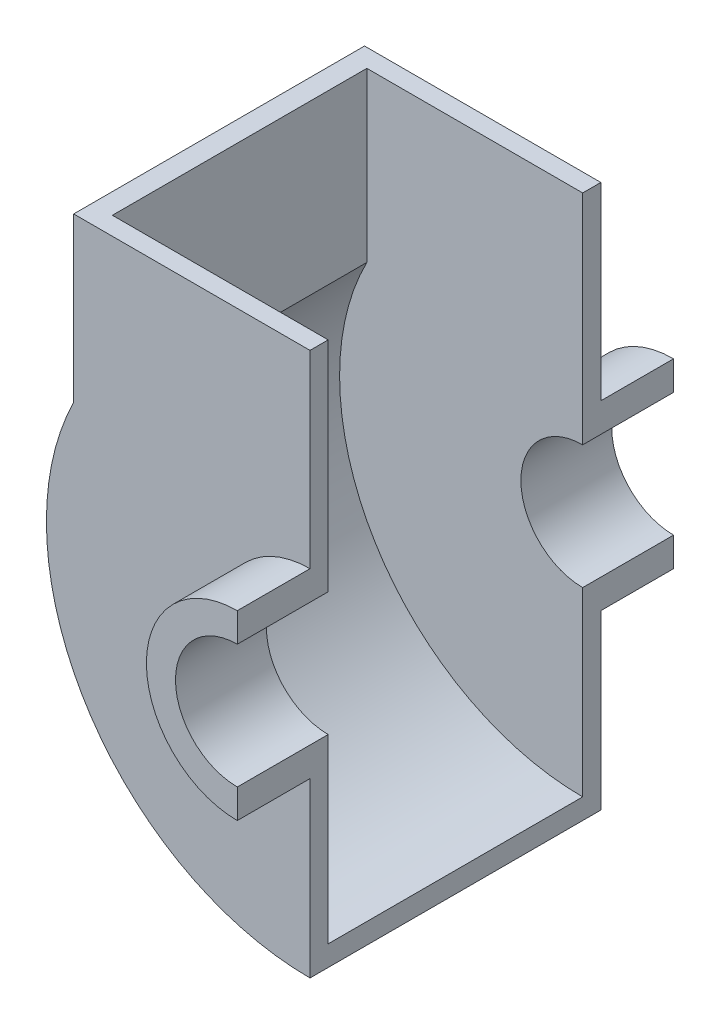
SolidWorks part; units mm, degrees
material "AISI 316 Annealed Stainless Steel Bar (SS)"
ref_plane "Front Plane" through (0, 0, 0) normal (0, 0, 1) x (1, 0, 0)
ref_plane "Top Plane" through (0, 0, 0) normal (0, 1, 0) x (1, 0, 0)
ref_plane "Right Plane" through (0, 0, 0) normal (1, 0, 0) x (0, 0, -1)
sketch "Sketch1" plane through (0, 0, 0) normal (0, 0, 1) x (1, 0, 0)
  line L1 (0, 25) -> (0, 17)
  line L2 (0, -17) -> (0, -25)
  arc A0 (0, 25) -> (0, -25) centre (0, 0) ccw
  arc A1 (0, 17) -> (0, -17) centre (0, 0) ccw
  dimension "D1" = 34
  dimension "D2" = 50
extrude "Boss-Extrude1" add sketch "Sketch1" along normal blind 20 and the other way blind 5
sketch "Sketch2" plane through (0, 0, 0) normal (0, 0, 1) x (1, 0, 0)
  line L0 (0, 25) -> (0, 77)
  line L1 (0, 77) -> (-65, 77)
  line L2 (-65, 77) -> (-65, 32.1131)
  line L3 (0, -25) -> (0, -72.5)
  arc A0 (-65, 32.1131) -> (0, -72.5) centre (0, 0) ccw
  arc A1 (0, 25) -> (0, -25) centre (0, 0) ccw construction
  arc A2 (0, 25) -> (0, -25) centre (0, 0) ccw
  point P11 (0, 77.1882)
  point P12 (-76.2824, 74.7729)
  point P13 (-77.2888, 90.9351)
  dimension "D1" = 145
  dimension "D2" = 52
  dimension "D3" = 65
extrude "Boss-Extrude2" add sketch "Sketch2" against normal blind 5
ref_plane "Plane1" through (0, 0, -40) normal (0, 0, 1) x (1, 0, 0)
mirror "Mirror4" about plane through (0, 0, -40) normal (0, 0, 1) of bodies 102
sketch "Sketch3" plane through (0, 0, -80) normal (0, 0, -1) x (-1, 0, 0)
  line L0 (65, 77) -> (65, 32.1131) construction
  line L1 (65, 77) -> (65, 32.1131)
  line L2 (59.36, 77) -> (59.36, 30.7677)
  line L3 (59.36, 77) -> (65, 77)
  line L4 (0, -66.86) -> (0, -72.5)
  arc A0 (0, -72.5) -> (65, 32.1131) centre (0, 0) ccw construction
  arc A1 (0, -72.5) -> (65, 32.1131) centre (0, 0) ccw
  arc A2 (0, -66.86) -> (59.36, 30.7677) centre (0, 0) ccw
  dimension "D1" = 5.64
extrude "Boss-Extrude3" add sketch "Sketch3" against normal up to body from offset 5
